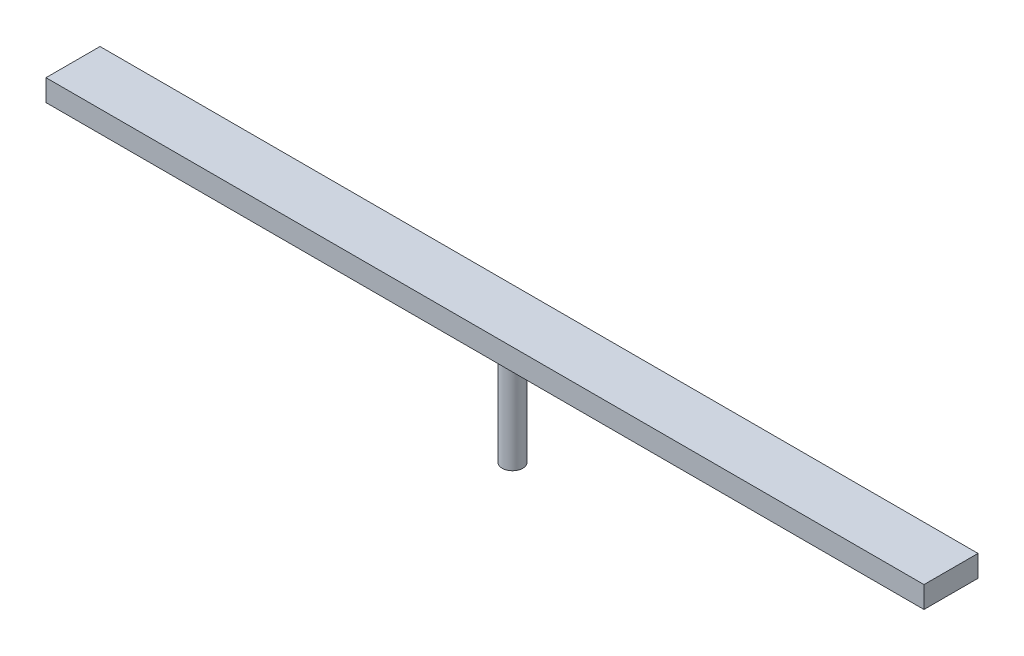
SolidWorks part; units mm, degrees
ref_plane "Front Plane" through (0, 0, 0) normal (0, 0, 1) x (1, 0, 0)
ref_plane "Top Plane" through (0, 0, 0) normal (0, 1, 0) x (1, 0, 0)
ref_plane "Right Plane" through (0, 0, 0) normal (1, 0, 0) x (0, 0, -1)
sketch "Sketch1" plane through (0, 0, 0) normal (0, 0, 1) x (1, 0, 0)
  line L0 (0, 0) -> (406.4, 0)
  line L1 (406.4, 0) -> (406.4, 10)
  line L2 (406.4, 10) -> (0, 10)
  line L3 (0, 10) -> (0, 0)
  dimension "D1" = 10
  dimension "D2" = 406.4
extrude "Boss-Extrude1" add sketch "Sketch1" along normal blind 25
sketch "Sketch2" plane through (0, 0, 0) normal (0, -1, 0) x (1, 0, 0)
  line L0 (0, 0) -> (406.4, 0) construction
  circle A0 centre (203.2, 12.25) radius 4.75
  dimension "D3" = 9.5
  dimension "D1" = 12.25
  dimension "D2" = 203.2
extrude "Boss-Extrude2" add sketch "Sketch2" along normal blind 49
